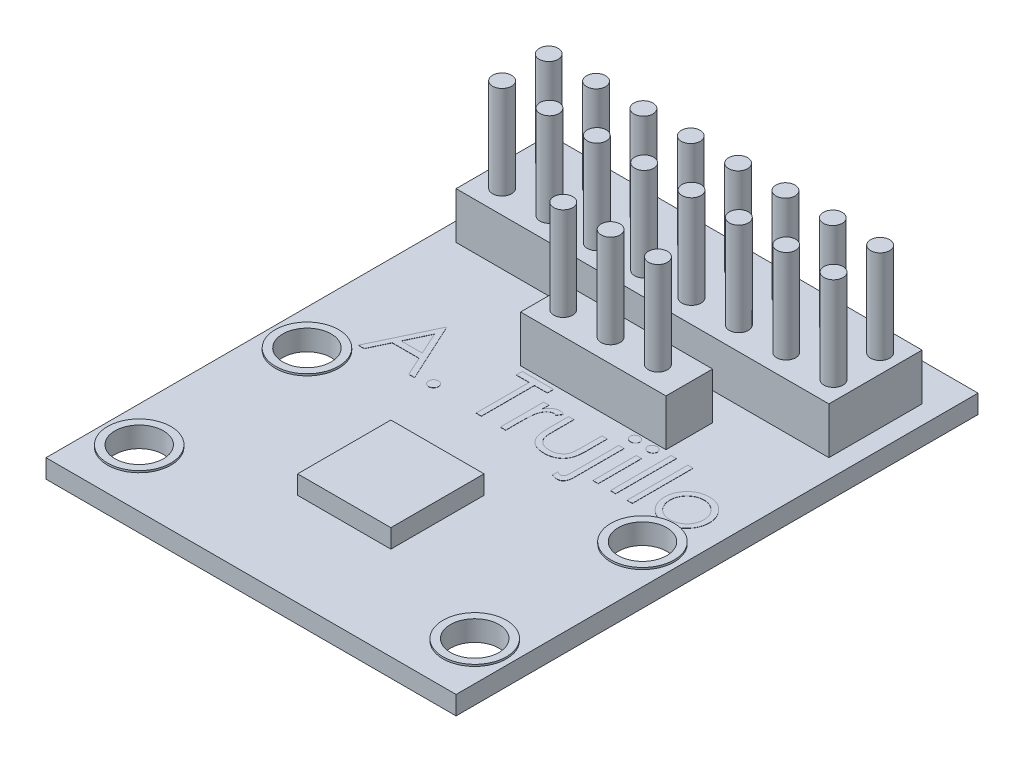
SolidWorks part; units mm, degrees
ref_plane "Front Plane" through (0, 0, 0) normal (0, 0, 1) x (1, 0, 0)
ref_plane "Top Plane" through (0, 0, 0) normal (0, 1, 0) x (1, 0, 0)
ref_plane "Right Plane" through (0, 0, 0) normal (1, 0, 0) x (0, 0, -1)
sketch "Sketch1" plane through (0, 0, 0) normal (0, 1, 0) x (1, 0, 0)
  line L1 (-11, 14) -> (11, 14)
  line L2 (-11, 14) -> (-11, -14)
  line L3 (-11, -14) -> (11, -14)
  line L4 (11, 14) -> (11, -14)
  line L5 (-11, 14) -> (11, -14) construction
  line L6 (-11, -14) -> (11, 14) construction
  point P0 (0, 0)
  dimension "D1" = 22
  dimension "D2" = 28
extrude "Boss-Extrude1" add sketch "Sketch1" along normal blind 1
sketch "Sketch2" plane through (0, 1, 0) normal (0, 1, 0) x (1, 0, 0)
  line L1 (-10, 12) -> (10, 12)
  line L2 (-10, 12) -> (-10, 7)
  line L3 (-10, 7) -> (10, 7)
  line L4 (10, 12) -> (10, 7)
  dimension "D1" = 10
  dimension "D2" = 7
  dimension "D3" = 5
  dimension "D4" = 20
extrude "Boss-Extrude2" add sketch "Sketch2" along normal blind 2.5
sketch "Sketch3" plane through (0, 3.5, 0) normal (0, 1, 0) x (1, 0, 0)
  line L0 (10, 9.5) -> (-10, 9.5) construction
  line L1 (10, 7) -> (10, 12) construction
  line L2 (-10, 12) -> (-10, 7) construction
  circle A0 centre (9, 8.25) radius 0.51
  circle A1 centre (6.46, 8.25) radius 0.51
  circle A2 centre (3.92, 8.25) radius 0.51
  circle A3 centre (1.38, 8.25) radius 0.51
  circle A4 centre (-1.16, 8.25) radius 0.51
  circle A5 centre (-3.7, 8.25) radius 0.51
  circle A6 centre (-6.24, 8.25) radius 0.51
  circle A7 centre (-8.78, 8.25) radius 0.51
  circle A8 centre (-8.78, 10.75) radius 0.51
  circle A9 centre (-6.24, 10.75) radius 0.51
  circle A10 centre (-3.7, 10.75) radius 0.51
  circle A11 centre (-1.16, 10.75) radius 0.51
  circle A12 centre (1.38, 10.75) radius 0.51
  circle A13 centre (3.92, 10.75) radius 0.51
  circle A14 centre (6.46, 10.75) radius 0.51
  circle A15 centre (9, 10.75) radius 0.51
  dimension "D1" = 1.02
  dimension "D2" = 9
  dimension "D3" = 8.25
  dimension "D4" = 8
extrude "Boss-Extrude3" add sketch "Sketch3" along normal blind 5
sketch "Sketch4" plane through (0, 1, 0) normal (0, 1, 0) x (1, 0, 0)
  line L1 (2.5, -9) -> (-2.5, -9)
  line L2 (2.5, -9) -> (2.5, -4)
  line L3 (2.5, -4) -> (-2.5, -4)
  line L4 (-2.5, -9) -> (-2.5, -4)
  point P4 (0, -4)
  dimension "D1" = 4
  dimension "D2" = 5
  dimension "D3" = 5
extrude "Boss-Extrude4" add sketch "Sketch4" along normal blind 1
sketch "Sketch5" plane through (0, 1, 0) normal (0, 1, 0) x (1, 0, 0)
  line L0 (0, 0) -> (0, -14) construction
  line L1 (-11, -14) -> (11, -14) construction
  line L2 (-11, -6.5) -> (11, -6.5) construction
  line L5 (-11, 14) -> (-11, -14) construction
  line L6 (11, -14) -> (11, 14) construction
  line L7 (-2.5, -4) -> (-2.5, -9) construction
  circle A0 centre (-9, -2) radius 1.3
  circle A1 centre (9, -2) radius 1.3
  circle A2 centre (9, -11) radius 1.3
  circle A3 centre (-9, -11) radius 1.3
  point P21 (-2.5, -6.5)
  dimension "D1" = 2.6
  dimension "D2" = 9
  dimension "D3" = 2
extrude "Cut-Extrude1" cut sketch "Sketch5" against normal blind 1
sketch "Sketch6" plane through (0, 1, 0) normal (0, 1, 0) x (1, 0, 0)
  circle A0 centre (-9, -11) radius 1.3 construction
  circle A1 centre (9, -11) radius 1.3 construction
  circle A2 centre (9, -2) radius 1.3 construction
  circle A3 centre (-9, -2) radius 1.3 construction
  circle A4 centre (-9, -11) radius 1.3
  circle A5 centre (9, -11) radius 1.3
  circle A6 centre (9, -2) radius 1.3
  circle A7 centre (-9, -2) radius 1.3
  circle A8 centre (-9, -2) radius 1.7
  circle A9 centre (9, -2) radius 1.7
  circle A10 centre (-9, -11) radius 1.7
  circle A11 centre (9, -11) radius 1.7
  dimension "D1" = 3.4
  dimension "D2" = 3.4
  dimension "D3" = 3.4
  dimension "D4" = 3.4
extrude "Boss-Extrude5" add sketch "Sketch6" along normal blind 0.1
sketch "Sketch7" plane through (0, 1, 0) normal (0, 1, 0) x (1, 0, 0)
  line L1 (-2.54, 5.5) -> (5.26, 5.5)
  line L2 (-2.54, 5.5) -> (-2.54, 3)
  line L3 (-2.54, 3) -> (5.26, 3)
  line L4 (5.26, 5.5) -> (5.26, 3)
  dimension "D1" = 2.5
  dimension "D2" = 7.8
  dimension "D3" = 3
  dimension "D4" = 2.54
extrude "Boss-Extrude6" add sketch "Sketch7" along normal blind 2.5
sketch "Sketch8" plane through (0, 3.5, 0) normal (0, 1, 0) x (1, 0, 0)
  line L0 (-2.54, 5.5) -> (-2.54, 3) construction
  circle A0 centre (-1.5, 4.25) radius 0.51
  circle A1 centre (1.04, 4.25) radius 0.51
  circle A2 centre (3.58, 4.25) radius 0.51
  point P5 (-2.54, 4.25)
  dimension "D3" = 1.02
  dimension "D1" = 1.5
  dimension "D2" = 3
extrude "Boss-Extrude7" add sketch "Sketch8" along normal blind 5
sketch "Sketch9" plane through (0, 1, 0) normal (0, 1, 0) x (1, 0, 0)
  text T0 "A. Trujillo"
  point P2 (0, 0)
  point P3 (0, 0)
  point P5 (0, 0)
  dimension "D1" = 8
  dimension "D2" = 3.6
extrude "Boss-Extrude8" add sketch "Sketch9" along normal blind 0.01
